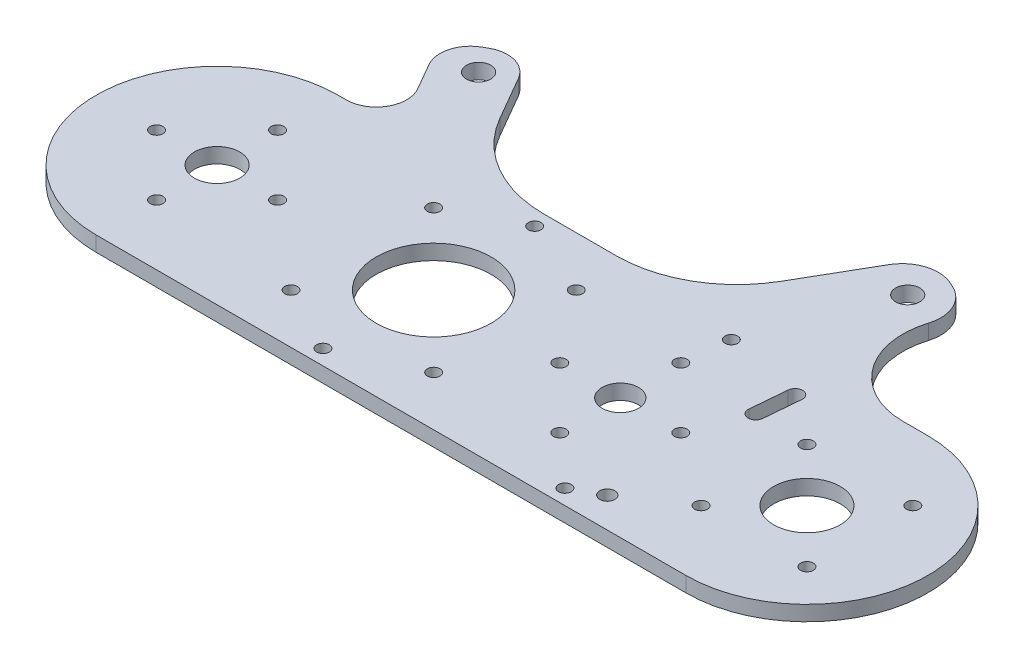
SolidWorks part; units mm, degrees
material "6061 Alloy"
ref_plane "Front Plane" through (0, 0, 0) normal (0, 0, 1) x (1, 0, 0)
ref_plane "Top Plane" through (0, 0, 0) normal (0, 1, 0) x (1, 0, 0)
ref_plane "Right Plane" through (0, 0, 0) normal (1, 0, 0) x (0, 0, -1)
sketch "Sketch1" plane through (0, 0, 0) normal (0, 1, 0) x (1, 0, 0)
  line L0 (-97.5, 0) -> (97.5, 0) construction
  line L1 (-97.5, 40) -> (97.5, 40)
  line L2 (-97.5, -40) -> (97.5, -40)
  line L3 (-27.5, 35) -> (37.5, 35) construction
  line L4 (-2.75, 0) -> (2.75, 0) construction
  line L5 (80, 17.5) -> (115, 17.5)
  line L6 (80, 17.5) -> (80, -17.5)
  line L7 (115, 17.5) -> (115, -17.5)
  line L8 (80, -17.5) -> (115, -17.5)
  line L9 (80, 17.5) -> (115, -17.5) construction
  line L10 (115, 17.5) -> (80, -17.5) construction
  arc A0 (-97.5, 40) -> (-97.5, -40) centre (-97.5, 0) ccw
  arc A1 (97.5, -40) -> (97.5, 40) centre (97.5, 0) ccw
  circle A2 centre (97.5, 0) radius 11
  circle A3 centre (-97.5, 0) radius 11
  circle A4 centre (35.8, 0) radius 6
  circle A5 centre (-97.5, 0) radius 7.5
  circle A6 centre (-97.5, 0) radius 20
  circle A7 centre (-97.5, 0) radius 20
  circle A8 centre (-97.5, -20) radius 2.1
  circle A9 centre (-117.5, 0) radius 2.1
  circle A10 centre (-97.5, 20) radius 2.1
  circle A11 centre (-77.5, 0) radius 2.1
  circle A12 centre (-25.9, 0) radius 19
  circle A13 centre (-27.5, 35) radius 2.1
  circle A14 centre (37.5, 35) radius 2.1
  circle A15 centre (52.5, -35) radius 2.1
  circle A16 centre (-27.5, -35) radius 2.1
  circle A17 centre (115, 17.5) radius 2.1
  circle A18 centre (115, -17.5) radius 2.1
  circle A19 centre (80, -17.5) radius 2.1
  circle A20 centre (80, 17.5) radius 2.1
  circle A21 centre (97.5, 0) radius 17.5 construction
  circle A27 centre (-25.9, 0) radius 33.333 construction
  circle A28 centre (-2.33, -23.57) radius 2.1
  circle A29 centre (-49.47, -23.57) radius 2.1
  circle A30 centre (-49.47, 23.57) radius 2.1
  circle A31 centre (-2.33, 23.57) radius 2.1
  circle A32 centre (35.8, 0) radius 20 construction
  circle A33 centre (55.8, 0) radius 2.1
  circle A34 centre (35.8, -20) radius 2.1
  circle A35 centre (15.8, 0) radius 2.1
  circle A36 centre (35.8, 20) radius 2.1
  circle A39 centre (61.5, -30) radius 2.5
  point P2 (0, 0)
  point P27 (-95, 0)
  point P61 (35.8, 0)
  point P64 (35.8, 0)
  point P73 (-25.9, 0)
  dimension "D2" = 40
  dimension "D3" = 22
  dimension "D4" = 22
  dimension "D5" = 12
  dimension "D7" = 40
  dimension "D8" = 15
  dimension "D9" = 4.2
  dimension "D10" = 40
  dimension "D11" = 38
  dimension "D13" = 65
  dimension "D14" = 4.2
  dimension "D18" = 35
  dimension "D17" = 4.2
  dimension "D20" = 4.2
  dimension "D22" = 4.2
  dimension "D26" = 80
  dimension "D1" = 195
  dimension "D6" = 61.7
  dimension "D12" = 61.7
  dimension "D15" = 5
  dimension "D16" = 70
  dimension "D23" = 20
  dimension "D24" = 35
  dimension "D25" = 35
  dimension "D29" = 10
  dimension "D21" = 4
  dimension "D19" = 4
extrude "Boss-Extrude1" add sketch "Sketch1" along normal blind 5
extrude "Cut-Extrude1" cut sketch "Sketch2" against normal blind 10
sketch "Sketch2" plane through (-432.7972, 0, 140.8967) normal (0, -1, 0) x (0, 0, -1)
  line L182 (143.4119, 425.4931) -> (140.4044, 424.626)
  line L183 (135.4529, 427.3614) -> (134.5858, 430.3689)
  line L184 (132.11, 431.7365) -> (98.3453, 422.002)
  line L185 (96.9776, 419.5262) -> (97.8447, 416.5187)
  line L186 (95.1093, 411.5671) -> (92.1018, 410.7001)
  line L187 (90.7341, 408.2243) -> (100.4687, 374.4596)
  line L188 (102.9445, 373.0919) -> (105.952, 373.959)
  line L189 (110.9035, 371.2236) -> (111.7706, 368.2161)
  line L190 (114.2464, 366.8484) -> (148.0111, 376.583)
  line L191 (149.3788, 379.0588) -> (148.5117, 382.0663)
  line L192 (155.6223, 390.3607) -> (145.8877, 424.1254)
  line L193 (151.2471, 387.0178) -> (154.2546, 387.8849)
  arc A173 (145.8877, 424.1254) -> (143.4119, 425.4931) centre (143.9659, 423.5714) ccw
  arc A174 (135.4529, 427.3614) -> (140.4044, 424.626) centre (139.2963, 428.4695) ccw
  arc A175 (134.5858, 430.3689) -> (132.11, 431.7365) centre (132.664, 429.8148) ccw
  arc A176 (98.3453, 422.002) -> (96.9776, 419.5262) centre (98.8993, 420.0802) ccw
  arc A177 (95.1093, 411.5671) -> (97.8447, 416.5187) centre (94.0012, 415.4106) ccw
  arc A178 (92.1018, 410.7001) -> (90.7341, 408.2243) centre (92.6558, 408.7783) ccw
  arc A179 (100.4687, 374.4596) -> (102.9445, 373.0919) centre (102.3904, 375.0136) ccw
  arc A180 (110.9035, 371.2236) -> (105.952, 373.959) centre (107.0601, 370.1155) ccw
  arc A181 (111.7706, 368.2161) -> (114.2464, 366.8484) centre (113.6923, 368.7701) ccw
  arc A182 (148.0111, 376.583) -> (149.3788, 379.0588) centre (147.4571, 378.5047) ccw
  arc A183 (154.2546, 387.8849) -> (155.6223, 390.3607) centre (153.7005, 389.8066) ccw
  arc A184 (151.2471, 387.0178) -> (148.5117, 382.0663) centre (152.3552, 383.1744) ccw
extrude "Cut-Extrude2" cut sketch "Sketch4" against normal blind 10
sketch "Sketch4" plane through (-704.648, 5, 167.2744) normal (0, 1, 0) x (0, 0, 1)
  circle A0 centre (364.7035, 640.8451) radius 14.142
extrude "Cut-Extrude3" cut sketch "Sketch5" against normal blind 10
sketch "Sketch5" plane through (-142.5934, 5, 362.8664) normal (0, 1, 0) x (0.8695, 0, 0.4939)
  circle A1 centre (-106.9667, 374.6111) radius 1
  circle A2 centre (-79.1889, 343.9263) radius 1
  circle A3 centre (-48.5041, 371.7041) radius 1
  circle A4 centre (-76.2819, 402.3889) radius 1
sketch "Sketch6" plane through (0, 5, 0) normal (0, 1, 0) x (1, 0, 0)
  line L0 (-52.5, 40) -> (-77.5, 83.3013)
  line L1 (-97.5, 40) -> (97.5, 40) construction
  line L2 (-77.5, 83.3013) -> (-96.25, 72.476)
  line L3 (-96.25, 72.476) -> (-77.5, 40)
  line L4 (-77.5, 40) -> (-52.5, 40)
  circle A2 centre (-80.8577, 69.8157) radius 4
  dimension "D1" = 8
  dimension "D5" = 10
  dimension "D6" = 12
  dimension "D2" = 120
  dimension "D3" = 20
  dimension "D4" = 25
  dimension "D7" = 50
extrude "Boss-Extrude2" add sketch "Sketch6" against normal blind 5
fillet "Fillet1" radius 10 3 edges at (-77.5, 2.5, -40) (-96.25, 2.5, -72.476) (-77.5, 2.5, -83.3013)
fillet "Fillet2" radius 40 1 edges at (-52.5, 2.5, -40)
sketch "Sketch8" plane through (0, 5, 0) normal (0, 1, 0) x (1, 0, 0)
  line L0 (62.7541, 17.8278) -> (63.8, 29.7821) construction
  line L1 (60.2636, 18.0457) -> (61.3095, 30)
  line L2 (65.2446, 17.6099) -> (66.2905, 29.5642)
  line L3 (-29.406, 40) -> (97.5, 40) construction
  arc A0 (60.2636, 18.0457) -> (65.2446, 17.6099) centre (62.7541, 17.8278) ccw
  arc A1 (66.2905, 29.5642) -> (61.3095, 30) centre (63.8, 29.7821) ccw
  point P2 (63.2771, 23.8049)
  dimension "D2" = 2.5
  dimension "D1" = 12
  dimension "D3" = 10
  dimension "D4" = 85
  dimension "D5" = 28
extrude "Cut-Extrude5" cut sketch "Sketch8" against normal through all
sketch "Sketch9" plane through (0, 5, 0) normal (0, 1, 0) x (1, 0, 0)
  line L0 (42.5, 40) -> (70.2487, 81.5934)
  line L1 (-29.406, 40) -> (97.5, 40) construction
  line L2 (70.2487, 81.5934) -> (47.5, 91.9615)
  line L3 (47.5, 91.9615) -> (17.5, 40)
  circle A0 centre (53.8509, 76.9615) radius 4
  line M37 (97.5, 40) -> (-29.406, 40)
  dimension "D4" = 8
  dimension "D5" = 13
  dimension "D6" = 15
  dimension "D1" = 55
  dimension "D2" = 25
  dimension "D3" = 60
  dimension "D7" = 120
  dimension "D8" = 50
extrude "Boss-Extrude3" add sketch "Sketch9" against normal blind 5 contours L2 L3 L0 A0 M37
fillet "Fillet4" radius 25 1 edges at (42.5, 2.5, -40)
fillet "Fillet6" radius 40 1 edges at (17.5, 2.5, -40)
fillet "Fillet7" radius 12 2 edges at (47.5, 2.5, -91.9615) (70.2487, 2.5, -81.5934)
